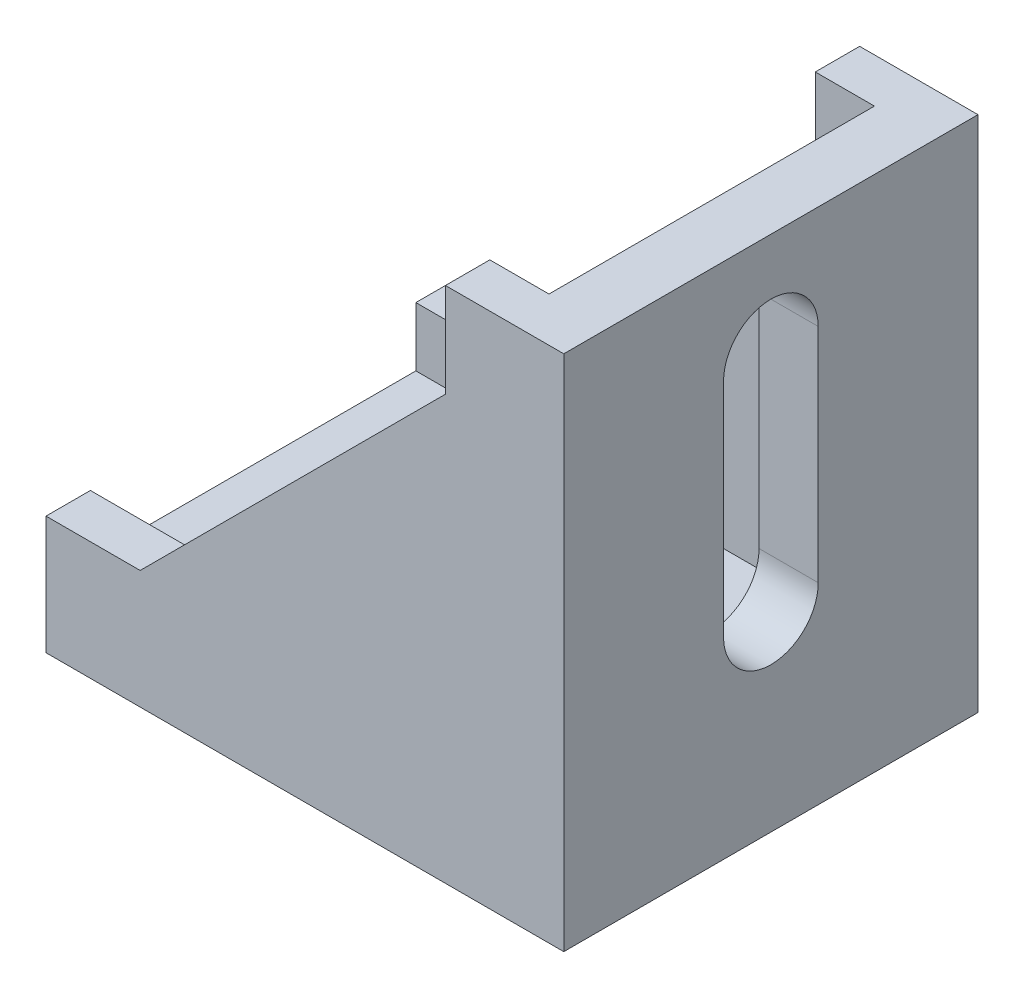
SolidWorks part; units mm, degrees
ref_plane "Front Plane" through (0, 0, 0) normal (0, 0, 1) x (1, 0, 0)
ref_plane "Top Plane" through (0, 0, 0) normal (0, 1, 0) x (1, 0, 0)
ref_plane "Right Plane" through (0, 0, 0) normal (1, 0, 0) x (0, 0, -1)
sketch "Sketch1" plane through (0, 0, 0) normal (0, 1, 0) x (1, 0, 0)
  line L1 (17.5, -14) -> (-17.5, -14)
  line L2 (17.5, -14) -> (17.5, 14)
  line L3 (17.5, 14) -> (-17.5, 14)
  line L4 (-17.5, -14) -> (-17.5, 14)
  line L5 (17.5, -14) -> (-17.5, 14) construction
  line L6 (17.5, 14) -> (-17.5, -14) construction
  point P0 (0, 0)
  dimension "D1" = 28
  dimension "D2" = 35
extrude "Boss-Extrude1" add sketch "Sketch1" along normal blind 35
sketch "Sketch2" plane through (0, 35, 0) normal (0, 1, 0) x (1, 0, 0)
  line L0 (17.5, -14) -> (17.5, 14) construction
  line L1 (13.5, 11) -> (-20.3068, 11)
  line L2 (13.5, 11) -> (13.5, -11)
  line L3 (13.5, -11) -> (-20.3068, -11)
  line L4 (-20.3068, 11) -> (-20.3068, -11)
  line L5 (13.5, 11) -> (-20.3068, -11) construction
  line L6 (13.5, -11) -> (-20.3068, 11) construction
  line L7 (17.5, 14) -> (-17.5, 14) construction
  line L8 (-17.5, -14) -> (17.5, -14) construction
  point P0 (-1.7521, 1.0746)
  dimension "D1" = 4
  dimension "D2" = 3
  dimension "D3" = 3
extrude "Cut-Extrude1" cut sketch "Sketch2" against normal offset from surface (31 mm away) 4 up to face at (0, 0, 0)
sketch "Sketch3" plane through (0, 0, 14) normal (0, 0, 1) x (1, 0, 0)
  line L0 (9.5, 35) -> (9.5, 28.6347)
  line L1 (-17.5, 35) -> (17.5, 35) construction
  line L2 (9.5, 28.6347) -> (-11.1347, 8)
  line L3 (-11.1347, 8) -> (-17.5, 8)
  line L4 (-17.5, 35) -> (-17.5, 0) construction
  line L5 (-17.5, 0) -> (17.5, 0) construction
  dimension "D1" = 135
  dimension "D2" = 8
  dimension "D3" = 6.3653
extrude "Cut-Extrude2" cut sketch "Sketch3" against normal through all and the other way through all flip side to cut
sketch "Sketch4" plane through (0, 4, 0) normal (0, 1, 0) x (1, 0, 0)
  line L0 (4.5, 0) -> (-10.5, 0) construction
  line L1 (4.5, -3.2) -> (-10.5, -3.2)
  line L2 (4.5, 3.2) -> (-10.5, 3.2)
  line L3 (-17.5, 11) -> (-17.5, -11) construction
  arc A0 (4.5, -3.2) -> (4.5, 3.2) centre (4.5, 0) ccw
  arc A1 (-10.5, 3.2) -> (-10.5, -3.2) centre (-10.5, 0) ccw
  point P2 (-3, 0)
  dimension "D1" = 6.4
  dimension "D2" = 15
  dimension "D3" = 7
extrude "Cut-Extrude3" cut sketch "Sketch4" against normal up to next
sketch "Sketch5" plane through (13.5, 23.5, 0) normal (-1, 0, 0) x (0, 1, 0)
  line L0 (4.5, 0) -> (-10.5, 0) construction
  line L1 (4.5, -3.2) -> (-10.5, -3.2)
  line L2 (4.5, 3.2) -> (-10.5, 3.2)
  line L3 (11.5, -11) -> (11.5, 11) construction
  arc A0 (4.5, -3.2) -> (4.5, 3.2) centre (4.5, 0) ccw
  arc A1 (-10.5, 3.2) -> (-10.5, -3.2) centre (-10.5, 0) ccw
  point P2 (-3, 0)
  dimension "D1" = 7
extrude "Cut-Extrude4" cut sketch "Sketch5" against normal up to next
